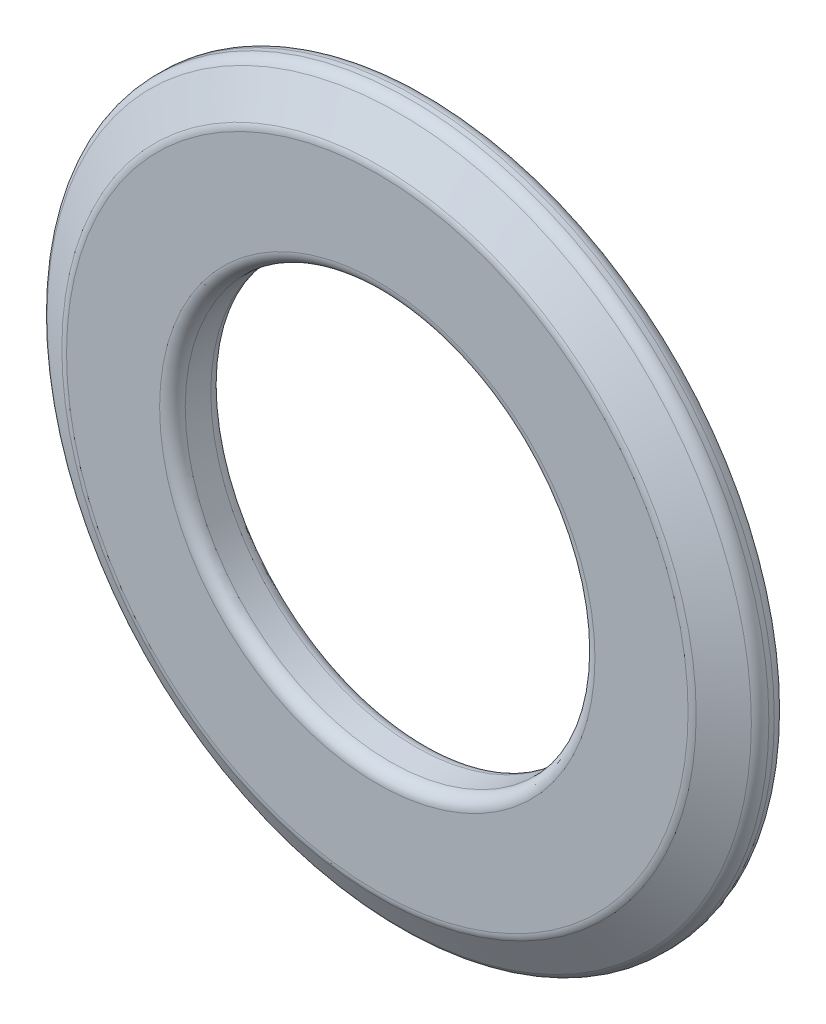
SolidWorks part; units mm, degrees
ref_plane "Front Plane" through (0, 0, 0) normal (0, 0, 1) x (1, 0, 0)
ref_plane "Top Plane" through (0, 0, 0) normal (0, 1, 0) x (1, 0, 0)
ref_plane "Right Plane" through (0, 0, 0) normal (1, 0, 0) x (0, 0, -1)
sketch "Sketch1" plane through (0, 0, 0) normal (0, 0, 1) x (1, 0, 0)
  circle A0 centre (15.23, -44.7825) radius 4
  circle A1 centre (15.23, -44.7825) radius 7
extrude "Boss-Extrude1" add sketch "Sketch1" along normal blind 1
chamfer "Chamfer1" distance 0.5 angle 60 1 edges at (22.23, -44.7825, 1)
fillet "Fillet1" radius 0.25 5 edges at (19.23, -44.7825, 0) (22.23, -44.7825, 0) (22.23, -44.7825, 0.5) (19.23, -44.7825, 1) (21.364, -44.7825, 1)
